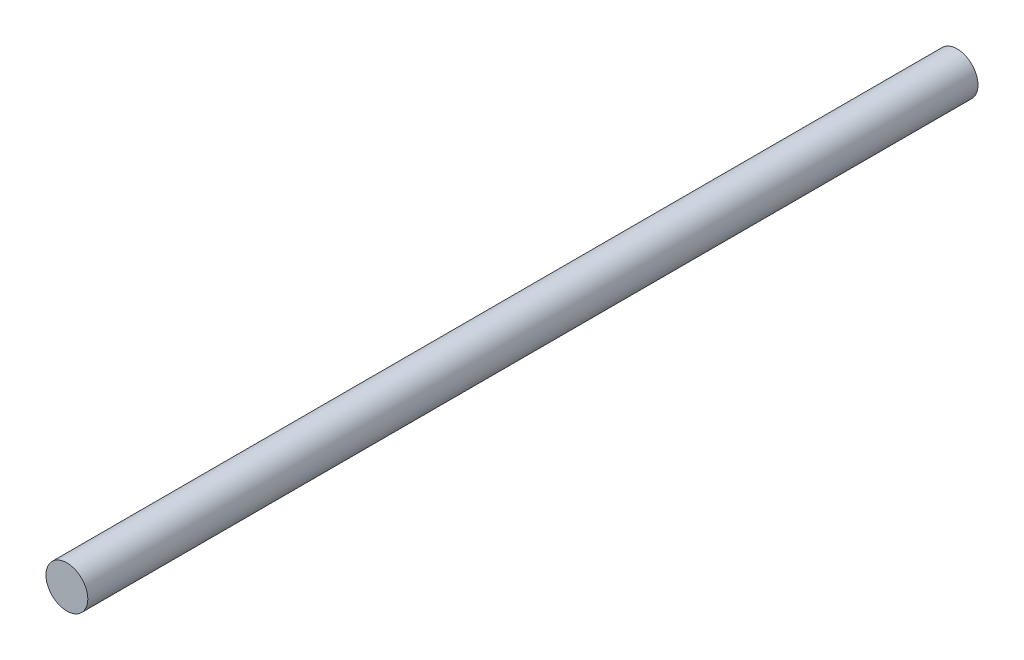
SolidWorks part; units mm, degrees
material "PVC Rigid"
ref_plane "Front Plane" through (0, 0, 0) normal (0, 0, 1) x (1, 0, 0)
ref_plane "Top Plane" through (0, 0, 0) normal (0, 1, 0) x (1, 0, 0)
ref_plane "Right Plane" through (0, 0, 0) normal (1, 0, 0) x (0, 0, -1)
sketch "Sketch2" plane through (0, 0, 0) normal (0, 0, 1) x (1, 0, 0)
  circle A0 centre (0, 0) radius 18.8
  dimension "D1" = 37.6
extrude "Boss-Extrude1" add sketch "Sketch2" against normal blind 800 contours A0
